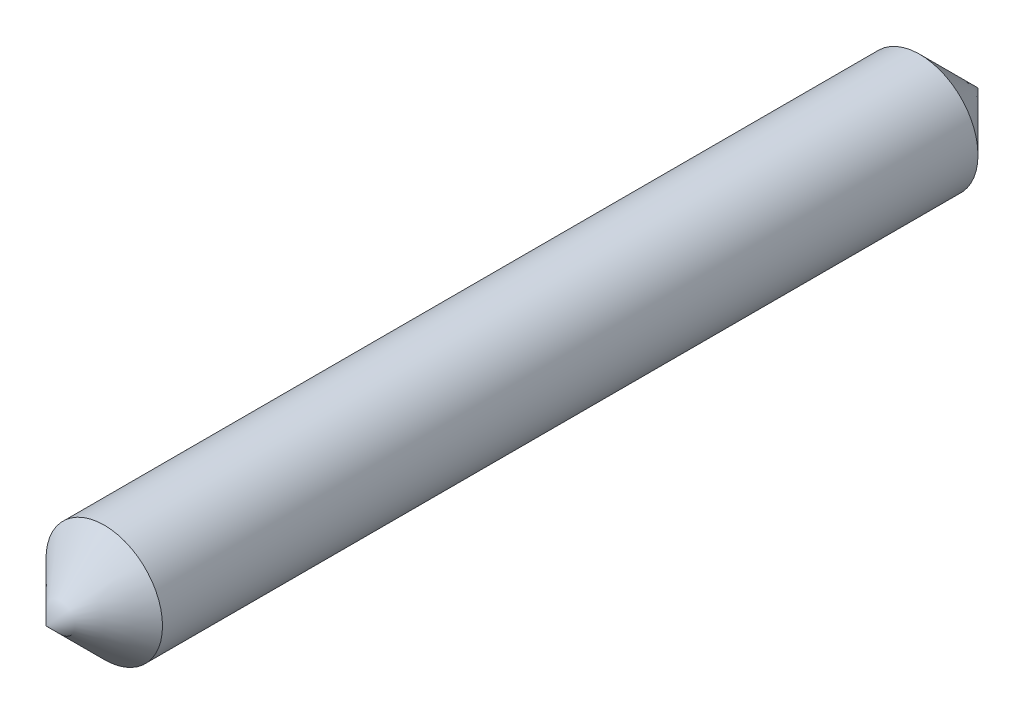
SolidWorks part; units mm, degrees
material "AISI 347 Annealed Stainless Steel (SS)"
ref_plane "Front Plane" through (0, 0, 0) normal (0, 0, 1) x (1, 0, 0)
ref_plane "Top Plane" through (0, 0, 0) normal (0, 1, 0) x (1, 0, 0)
ref_plane "Right Plane" through (0, 0, 0) normal (1, 0, 0) x (0, 0, -1)
sketch "Sketch1" plane through (0, 0, 0) normal (0, 0, 1) x (1, 0, 0)
  circle A0 centre (0, 0) radius 0.625
  dimension "D1" = 1.25
extrude "Boss-Extrude1" add sketch "Sketch1" along normal blind 10
chamfer "Chamfer1" distance 0.625 angle 45 2 edges at (0.625, 0, 0) (0.625, 0, 10)
